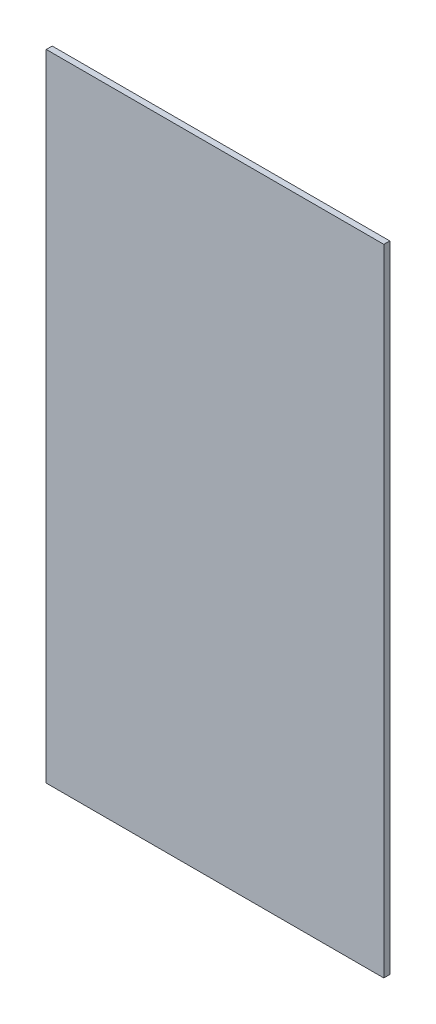
SolidWorks part; units mm, degrees
ref_plane "Alzado" through (0, 0, 0) normal (0, 0, 1) x (1, 0, 0)
ref_plane "Planta" through (0, 0, 0) normal (0, 1, 0) x (1, 0, 0)
ref_plane "Vista lateral" through (0, 0, 0) normal (1, 0, 0) x (0, 0, -1)
sketch "Croquis2" plane through (0, 0, 0) normal (0, 0, 1) x (1, 0, 0)
  line L1 (-85, 160) -> (85, 160)
  line L2 (-85, 160) -> (-85, -160)
  line L3 (-85, -160) -> (85, -160)
  line L4 (85, 160) -> (85, -160)
  dimension "D1" = 170
  dimension "D2" = 320
  dimension "D3" = 160
  dimension "D4" = 85
extrude "Saliente-Extruir1" add sketch "Croquis2" along normal blind 3
